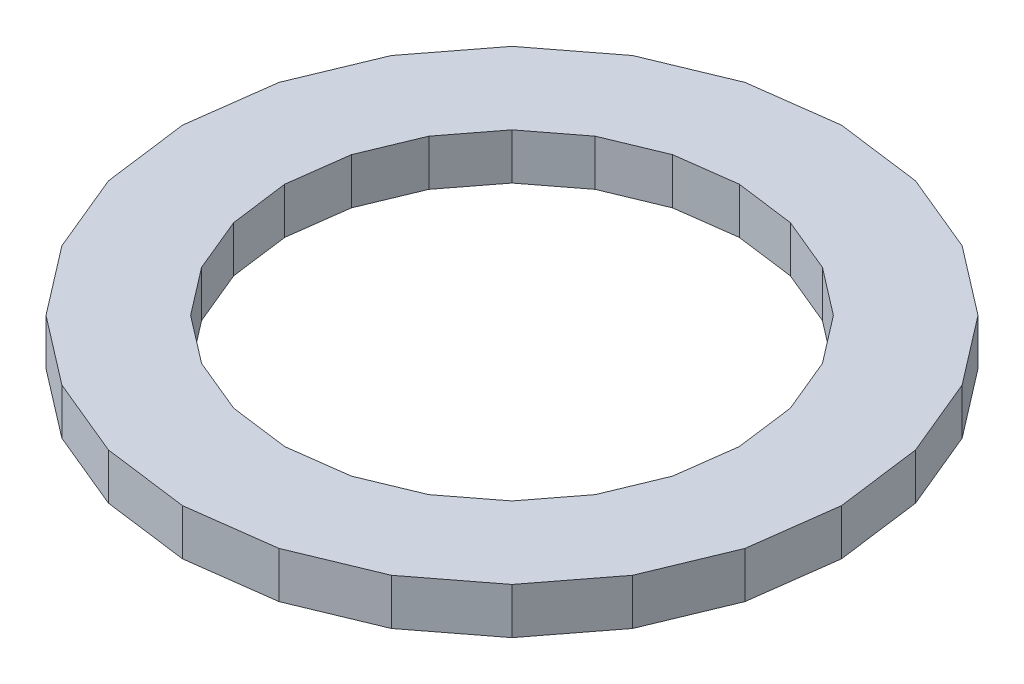
SolidWorks part; units mm, degrees
ref_plane "Front Plane" through (0, 0, 0) normal (0, 0, 1) x (1, 0, 0)
ref_plane "Top Plane" through (0, 0, 0) normal (0, 1, 0) x (1, 0, 0)
ref_plane "Right Plane" through (0, 0, 0) normal (1, 0, 0) x (0, 0, -1)
sketch "Sketch3" plane through (0, 0, 0) normal (0, 1, 0) x (1, 0, 0)
  line L0 (0, 0) -> (-93.9462, 0) construction
  line L1 (-136.2179, 0) -> (-131.5764, -35.2558)
  line L2 (-131.5764, -35.2558) -> (-117.9681, -68.1089)
  line L3 (-117.9681, -68.1089) -> (-96.3206, -96.3206)
  line L4 (-96.3206, -96.3206) -> (-68.1089, -117.9681)
  line L5 (-68.1089, -117.9681) -> (-35.2558, -131.5764)
  line L6 (-35.2558, -131.5764) -> (0, -136.2179)
  line L7 (0, -136.2179) -> (35.2558, -131.5764)
  line L8 (35.2558, -131.5764) -> (68.1089, -117.9681)
  line L9 (68.1089, -117.9681) -> (96.3206, -96.3206)
  line L10 (96.3206, -96.3206) -> (117.9681, -68.1089)
  line L11 (117.9681, -68.1089) -> (131.5764, -35.2558)
  line L12 (131.5764, -35.2558) -> (136.2179, 0)
  line L13 (136.2179, 0) -> (131.5764, 35.2558)
  line L14 (131.5764, 35.2558) -> (117.9681, 68.1089)
  line L15 (117.9681, 68.1089) -> (96.3206, 96.3206)
  line L16 (96.3206, 96.3206) -> (68.1089, 117.9681)
  line L17 (68.1089, 117.9681) -> (35.2558, 131.5764)
  line L18 (35.2558, 131.5764) -> (0, 136.2179)
  line L19 (0, 136.2179) -> (-35.2558, 131.5764)
  line L20 (-35.2558, 131.5764) -> (-68.1089, 117.9681)
  line L21 (-68.1089, 117.9681) -> (-96.3206, 96.3206)
  line L22 (-96.3206, 96.3206) -> (-117.9681, 68.1089)
  line L23 (-117.9681, 68.1089) -> (-131.5764, 35.2558)
  line L24 (-131.5764, 35.2558) -> (-136.2179, 0)
  line L25 (-93.9462, 0) -> (-90.7451, -24.3151)
  line L26 (-90.7451, -24.3151) -> (-81.3598, -46.9731)
  line L27 (-81.3598, -46.9731) -> (-66.43, -66.43)
  line L28 (-66.43, -66.43) -> (-46.9731, -81.3598)
  line L29 (-46.9731, -81.3598) -> (-24.3151, -90.7451)
  line L30 (-24.3151, -90.7451) -> (0, -93.9462)
  line L31 (0, -93.9462) -> (24.3151, -90.7451)
  line L32 (24.3151, -90.7451) -> (46.9731, -81.3598)
  line L33 (46.9731, -81.3598) -> (66.43, -66.43)
  line L34 (66.43, -66.43) -> (81.3598, -46.9731)
  line L35 (81.3598, -46.9731) -> (90.7451, -24.3151)
  line L36 (90.7451, -24.3151) -> (93.9462, 0)
  line L37 (93.9462, 0) -> (90.7451, 24.3151)
  line L38 (90.7451, 24.3151) -> (81.3598, 46.9731)
  line L39 (81.3598, 46.9731) -> (66.43, 66.43)
  line L40 (66.43, 66.43) -> (46.9731, 81.3598)
  line L41 (46.9731, 81.3598) -> (24.3151, 90.7451)
  line L42 (24.3151, 90.7451) -> (0, 93.9462)
  line L43 (0, 93.9462) -> (-24.3151, 90.7451)
  line L44 (-24.3151, 90.7451) -> (-46.9731, 81.3598)
  line L45 (-46.9731, 81.3598) -> (-66.43, 66.43)
  line L46 (-66.43, 66.43) -> (-81.3598, 46.9731)
  line L47 (-81.3598, 46.9731) -> (-90.7451, 24.3151)
  line L48 (-90.7451, 24.3151) -> (-93.9462, 0)
  line L49 (-136.2179, 0) -> (-93.9462, 0) construction
  circle A0 centre (0, 0) radius 135.0525 construction
  circle A1 centre (0, 0) radius 93.1425 construction
  dimension "D1" = 35.56
  dimension "D2" = 41.91
extrude "Boss-Extrude3" add sketch "Sketch3" along normal blind 19.05
